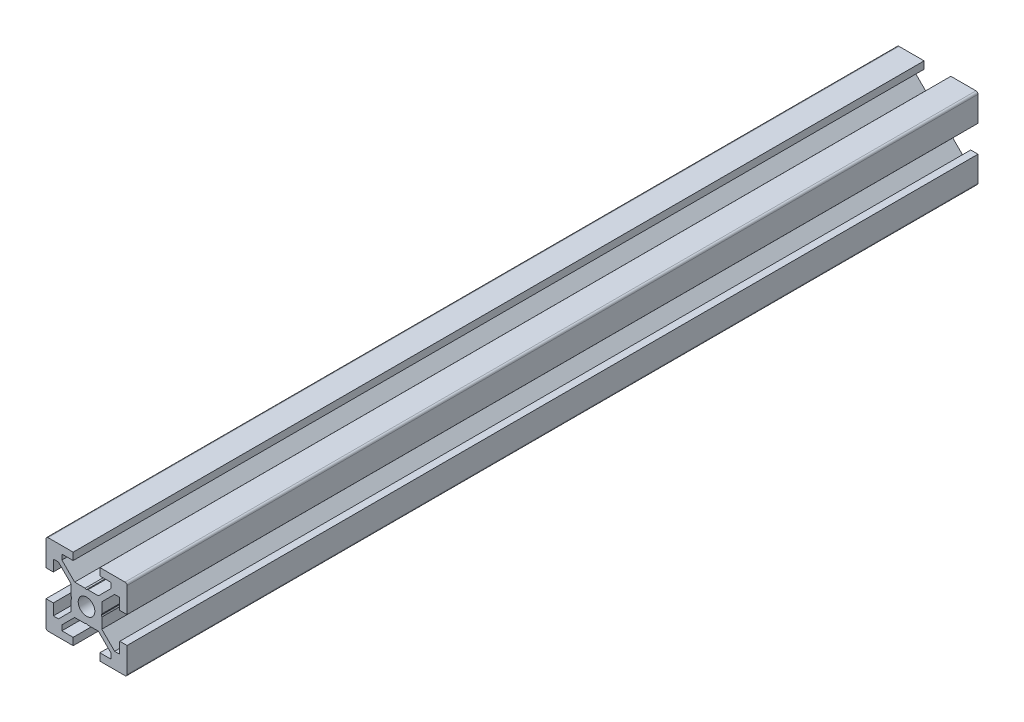
SolidWorks part; units mm, degrees
ref_plane "Front Plane" through (0, 0, 0) normal (0, 0, 1) x (1, 0, 0)
ref_plane "Top Plane" through (0, 0, 0) normal (0, 1, 0) x (1, 0, 0)
ref_plane "Right Plane" through (0, 0, 0) normal (1, 0, 0) x (0, 0, -1)
sketch "Sketch1" plane through (0, 0, 0) normal (0, 0, 1) x (1, 0, 0)
  line L0 (-3.3, 10) -> (-3.3, 8.2)
  line L1 (0, 0) -> (50000, 0) construction
  line L2 (-10, 3.3) -> (-10, 10)
  line L3 (-10, 10) -> (-3.3, 10)
  line L4 (0, 0) -> (0, 50000) construction
  line L5 (-10, -10) -> (10, 10) construction
  line L6 (-10, 10) -> (10, -10) construction
  line L7 (-2.9315, -3.78) -> (-0.34, -3.78)
  line L8 (-3.78, -2.9315) -> (-3.78, -0.34)
  line L9 (-2.9315, 3.78) -> (-0.34, 3.78)
  line L10 (3.78, -2.9315) -> (3.78, -0.34)
  line L11 (-3.78, -3.78) -> (3.78, 3.78) construction
  line L12 (-3.78, 3.78) -> (3.78, -3.78) construction
  line L13 (-6.08, 8.2) -> (-3.3, 8.2)
  line L14 (-8.2, 6.08) -> (-8.2, 3.3)
  line L15 (-8.2, 3.3) -> (-10, 3.3)
  line L16 (-8.2, 6.08) -> (-6.9285, 6.08)
  line L17 (-6.08, 8.2) -> (-6.08, 6.9285)
  line L18 (-6.9285, 6.08) -> (-3.78, 2.9315)
  line L19 (-6.08, 6.9285) -> (-2.9315, 3.78)
  line L20 (8.2, 6.08) -> (6.9285, 6.08)
  line L21 (8.2, 6.08) -> (8.2, 3.3)
  line L22 (8.2, 3.3) -> (10, 3.3)
  line L23 (10, 3.3) -> (10, 10)
  line L24 (10, 10) -> (3.3, 10)
  line L25 (3.3, 10) -> (3.3, 8.2)
  line L26 (6.08, 8.2) -> (3.3, 8.2)
  line L27 (6.08, 8.2) -> (6.08, 6.9285)
  line L28 (6.08, 6.9285) -> (2.9315, 3.78)
  line L29 (6.9285, 6.08) -> (3.78, 2.9315)
  line L30 (6.9285, -6.08) -> (3.78, -2.9315)
  line L31 (6.08, -6.9285) -> (2.9315, -3.78)
  line L32 (6.08, -8.2) -> (6.08, -6.9285)
  line L33 (6.08, -8.2) -> (3.3, -8.2)
  line L34 (3.3, -10) -> (3.3, -8.2)
  line L35 (10, -10) -> (3.3, -10)
  line L36 (10, -3.3) -> (10, -10)
  line L37 (8.2, -3.3) -> (10, -3.3)
  line L38 (8.2, -6.08) -> (8.2, -3.3)
  line L39 (8.2, -6.08) -> (6.9285, -6.08)
  line L40 (-6.08, -6.9285) -> (-2.9315, -3.78)
  line L41 (-6.9285, -6.08) -> (-3.78, -2.9315)
  line L42 (-6.08, -8.2) -> (-6.08, -6.9285)
  line L43 (-8.2, -6.08) -> (-6.9285, -6.08)
  line L44 (-8.2, -3.3) -> (-10, -3.3)
  line L45 (-8.2, -6.08) -> (-8.2, -3.3)
  line L46 (-6.08, -8.2) -> (-3.3, -8.2)
  line L47 (-10, -10) -> (-3.3, -10)
  line L48 (-10, -3.3) -> (-10, -10)
  line L49 (-3.3, -10) -> (-3.3, -8.2)
  line L50 (-0.34, 3.78) -> (0, 3.66)
  line L51 (0.34, 3.78) -> (0, 3.66)
  line L52 (0.34, 3.78) -> (2.9315, 3.78)
  line L53 (-3.78, -0.34) -> (-3.66, 0)
  line L54 (-3.78, 0.34) -> (-3.66, 0)
  line L55 (3.78, 0.34) -> (3.66, 0)
  line L56 (3.78, -0.34) -> (3.66, 0)
  line L57 (-0.34, -3.78) -> (0, -3.66)
  line L58 (0.34, -3.78) -> (0, -3.66)
  line L59 (3.78, 0.34) -> (3.78, 2.9315)
  line L60 (0.34, -3.78) -> (2.9315, -3.78)
  line L61 (-3.78, 0.34) -> (-3.78, 2.9315)
  circle A0 centre (0, 0) radius 2.05
  point P0 (0, 0)
  dimension "D3" = 4.1
  dimension "D1" = 20
  dimension "D2" = 20
  dimension "D4" = 7.56
  dimension "D5" = 6.7
  dimension "D6" = 6.7
  dimension "D7" = 0.6
  dimension "D8" = 3.92
  dimension "D9" = 0.34
  dimension "D10" = 0.12
extrude "Boss-Extrude1" add sketch "Sketch1" along normal blind 210
fillet "Fillet1" radius 0.5 4 edges at (-10, 10, 105) (-10, -10, 105) (10, -10, 105) (10, 10, 105)
sketch "Sketch2" plane through (3.78, 0, 0) normal (1, 0, 0) x (0, 0, -1)
  line L0 (-2.8944, 0) -> (-50002.8944, 0) construction
  line L2 (0, -9.5) -> (0, -3.3) construction
  circle A0 centre (-3.95, 0) radius 2.25
  circle A1 centre (-52.55, 0) radius 2.25
  dimension "D1" = 4.5
  dimension "D2" = 4.5
  dimension "D3" = 3.95
  dimension "D4" = 52.55
extrude "Cut-Extrude1" cut sketch "Sketch2" against normal up to next
